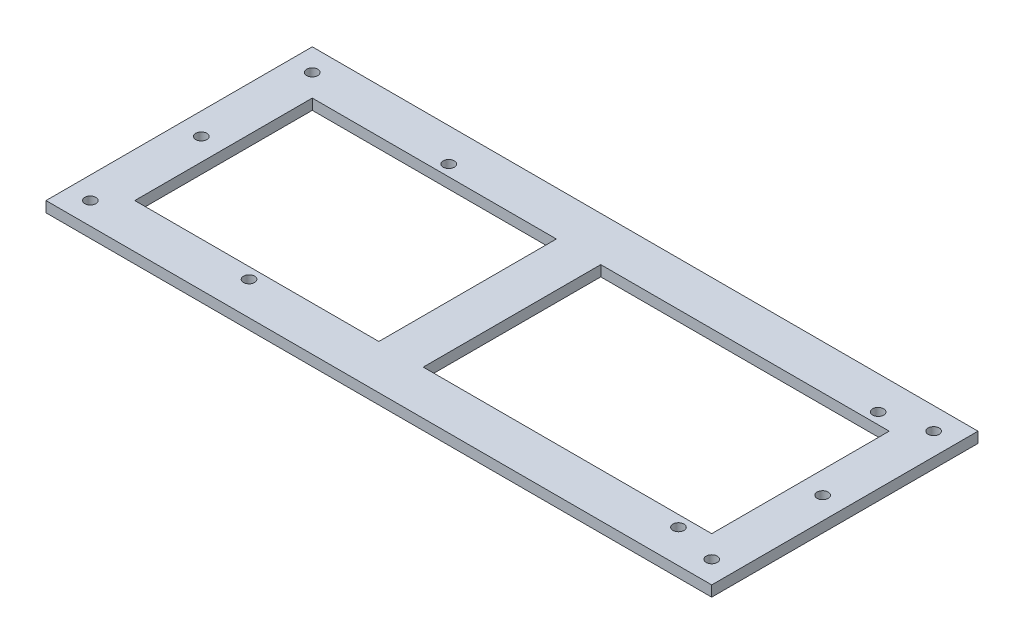
SolidWorks part; units mm, degrees
ref_plane "Front Plane" through (0, 0, 0) normal (0, 0, 1) x (1, 0, 0)
ref_plane "Top Plane" through (0, 0, 0) normal (0, 1, 0) x (1, 0, 0)
ref_plane "Right Plane" through (0, 0, 0) normal (1, 0, 0) x (0, 0, -1)
sketch "Sketch1" plane through (0, 0, 0) normal (0, 1, 0) x (1, 0, 0)
  line L1 (0, 0) -> (-190.5, 0)
  line L2 (0, 0) -> (0, -76.2)
  line L3 (0, -76.2) -> (-190.5, -76.2)
  line L4 (-190.5, 0) -> (-190.5, -76.2)
  dimension "D1" = 76.2
  dimension "D2" = 190.5
extrude "Boss-Extrude1" add sketch "Sketch1" along normal blind 3.048
sketch "Sketch2" plane through (0, 3.048, 0) normal (0, 1, 0) x (1, 0, 0)
  line L0 (0, -76.2) -> (0, 0) construction
  line L1 (-12.7, -12.7) -> (-95.25, -12.7)
  line L2 (-12.7, -12.7) -> (-12.7, -63.5)
  line L3 (-12.7, -63.5) -> (-95.25, -63.5)
  line L4 (-95.25, -12.7) -> (-95.25, -63.5)
  line L5 (0, 0) -> (-190.5, 0) construction
  line L6 (-190.5, -76.2) -> (0, -76.2) construction
  line L7 (-107.95, -12.7) -> (-177.8, -12.7)
  line L8 (-107.95, -12.7) -> (-107.95, -63.5)
  line L9 (-107.95, -63.5) -> (-177.8, -63.5)
  line L10 (-177.8, -12.7) -> (-177.8, -63.5)
  line L11 (-190.5, 0) -> (-190.5, -76.2) construction
  point P4 (0, -38.1)
  point P15 (-190.5, -38.1)
  dimension "D1" = 12.7
  dimension "D2" = 12.7
  dimension "D3" = 50.8
  dimension "D4" = 82.55
  dimension "D5" = 12.7
  dimension "D6" = 12.7
  dimension "D7" = 12.7
  dimension "D8" = 12.7
extrude "Cut-Extrude1" cut sketch "Sketch2" against normal blind 3.048
sketch "Sketch3" plane through (0, 3.048, 0) normal (0, 1, 0) x (1, 0, 0)
  line L0 (0, -76.2) -> (0, 0) construction
  line L1 (-190.5, -76.2) -> (0, -76.2) construction
  line L2 (-190.5, 0) -> (-190.5, -76.2) construction
  line L3 (0, 0) -> (-190.5, 0) construction
  line L4 (-190.5, 0) -> (-190.5, -76.2) construction
  circle A0 centre (-6.35, -38.1) radius 1.5875
  circle A1 centre (-184.1682, -38.1) radius 1.5875
  circle A2 centre (-6.35, -6.35) radius 1.5875
  circle A3 centre (-184.1682, -6.35) radius 1.5875
  circle A4 centre (-184.1682, -69.85) radius 1.5875
  circle A5 centre (-6.35, -69.85) radius 1.5875
  circle A6 centre (-19.05, -9.525) radius 1.5875
  circle A7 centre (-19.05, -66.675) radius 1.5875
  circle A8 centre (-141.9225, -9.525) radius 1.5875
  circle A9 centre (-141.9225, -66.675) radius 1.5875
  point P8 (-190.5, -38.1)
  dimension "D3" = 3.175
  dimension "D5" = 3.175
  dimension "D6" = 6.35
  dimension "D8" = 3.175
  dimension "D9" = 3.175
  dimension "D11" = 3.175
  dimension "D12" = 6.35
  dimension "D13" = 3.175
  dimension "D16" = 3.175
  dimension "D18" = 3.175
  dimension "D20" = 3.175
  dimension "D21" = 3.175
  dimension "D1" = 6.35
  dimension "D2" = 38.1
  dimension "D4" = 6.3318
  dimension "D7" = 6.3318
  dimension "D10" = 6.35
  dimension "D14" = 19.05
  dimension "D15" = 9.525
  dimension "D17" = 9.525
  dimension "D19" = 141.9225
extrude "Cut-Extrude2" cut sketch "Sketch3" against normal blind 3.048
